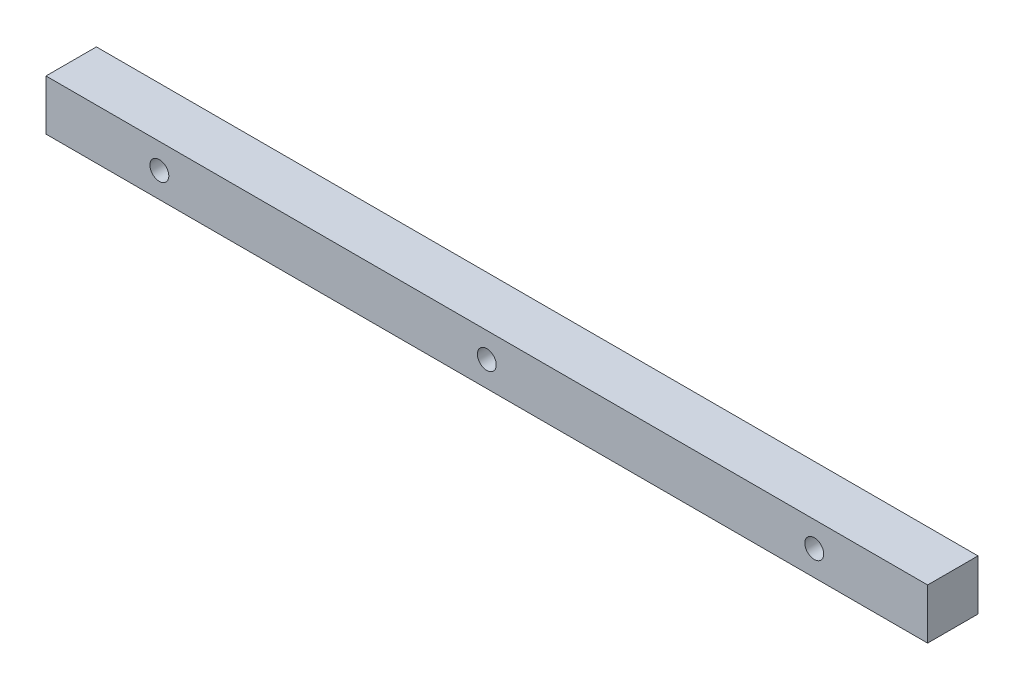
SolidWorks part; units mm, degrees
ref_plane "前视基准面" through (0, 0, 0) normal (0, 0, 1) x (1, 0, 0)
ref_plane "上视基准面" through (0, 0, 0) normal (0, 1, 0) x (1, 0, 0)
ref_plane "右视基准面" through (0, 0, 0) normal (1, 0, 0) x (0, 0, -1)
sketch "草图1" plane through (0, 0, 0) normal (0, 0, 1) x (1, 0, 0)
  line L0 (0, 4) -> (140, 4) construction
  line L1 (0, 0) -> (140, 0)
  line L2 (0, 0) -> (0, 8)
  line L3 (0, 8) -> (140, 8)
  line L4 (140, 0) -> (140, 8)
  line L5 (70, 8) -> (70, 0) construction
  circle A0 centre (70, 4) radius 1.5
  circle A1 centre (18, 4) radius 1.5
  circle A2 centre (122, 4) radius 1.5
  dimension "D3" = 3
  dimension "D4" = 3
  dimension "D1" = 140
  dimension "D2" = 8
  dimension "D5" = 52
extrude "凸台-拉伸1" add sketch "草图1" along normal blind 8
